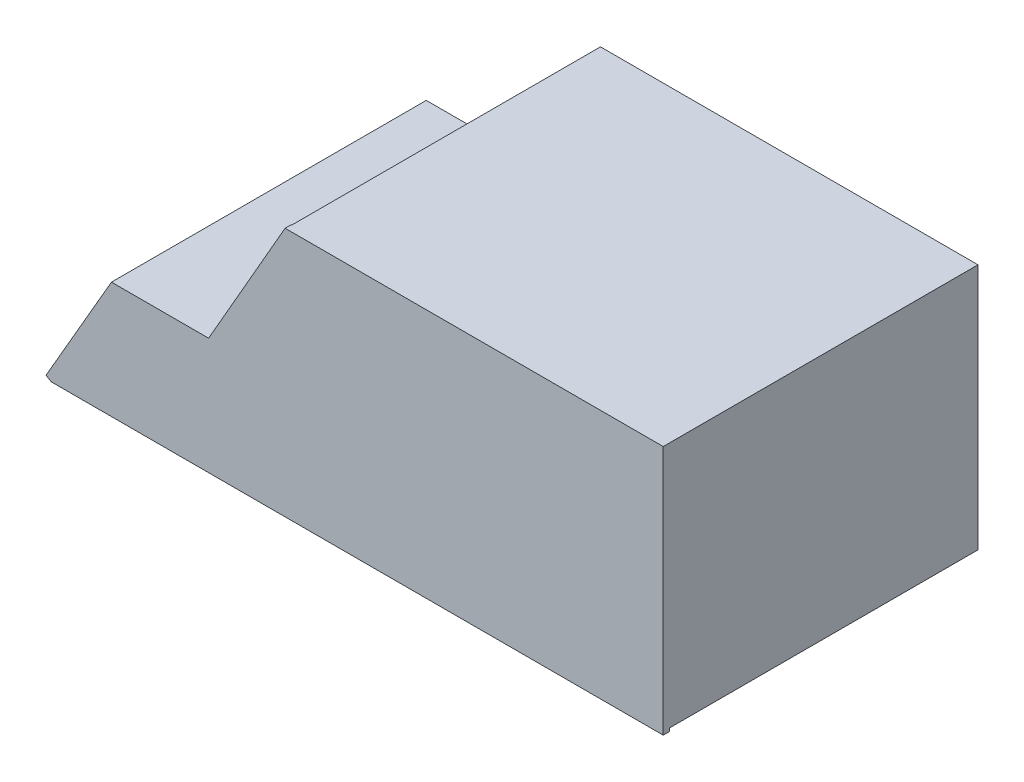
SolidWorks part; units mm, degrees
ref_plane "Plan de face" through (0, 0, 0) normal (0, 0, 1) x (1, 0, 0)
ref_plane "Plan de dessus" through (0, 0, 0) normal (0, 1, 0) x (1, 0, 0)
ref_plane "Plan de droite" through (0, 0, 0) normal (1, 0, 0) x (0, 0, -1)
sketch "Esquisse1" plane through (0, 0, 0) normal (0, 0, 1) x (1, 0, 0)
  line L0 (-49.5855, -0.3633) -> (-28.3723, 36.3791)
  line L1 (-28.3723, 36.3791) -> (3.1087, 36.3791)
  line L2 (3.1087, 36.3791) -> (28.0835, 79.6367)
  line L3 (28.0835, 79.6367) -> (150.4145, 79.6367)
  line L4 (150.4145, 79.6367) -> (150.4145, -0.3633)
  line L5 (-49.5855, -0.3633) -> (150.4145, -0.3633) construction
  point P2 (93.9688, 38.102)
  dimension "D1" = 200
  dimension "D2" = 80
  dimension "D3" = 120
extrude "Extru.-Mince1" add sketch "Esquisse1" along normal blind 100 thin
sketch "Esquisse2" plane through (0, 0, 100) normal (0, 0, 1) x (1, 0, 0)
  line L0 (27.9114, -1.3633) -> (-47.8534, -1.3633)
  line L1 (150.4145, 79.6367) -> (27.8991, 79.6367)
  line L2 (150.4145, 79.6367) -> (150.4145, -1.3633)
  line L3 (150.4145, -1.3633) -> (27.9114, -1.3633)
  line L5 (-47.8534, -1.3633) -> (-49.5855, -0.3633)
  line L6 (-49.5855, -0.3633) -> (-28.3723, 36.3791)
  line L7 (-28.3723, 36.3791) -> (3.1087, 36.3791)
  line L8 (3.1087, 36.3791) -> (27.8991, 79.6367)
extrude "Extrusion2" add sketch "Esquisse2" along normal blind 2
